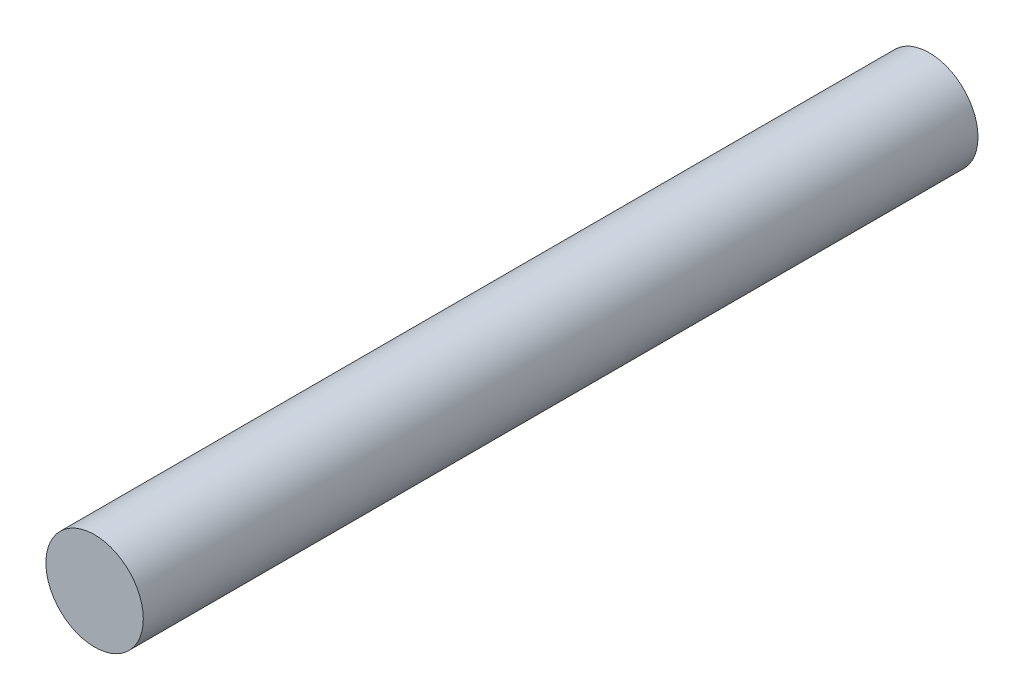
SolidWorks part; units mm, degrees
ref_plane "Front Plane" through (0, 0, 0) normal (0, 0, 1) x (1, 0, 0)
ref_plane "Top Plane" through (0, 0, 0) normal (0, 1, 0) x (1, 0, 0)
ref_plane "Right Plane" through (0, 0, 0) normal (1, 0, 0) x (0, 0, -1)
other "Configuration Table"
sketch "Sketch1" plane through (0, 0, 0) normal (0, 0, 1) x (1, 0, 0)
  circle A0 centre (0, 68) radius 35
extrude "KAP_helezon_POM_D70" add sketch "Sketch1" against normal blind 600 from offset 100 separate body
